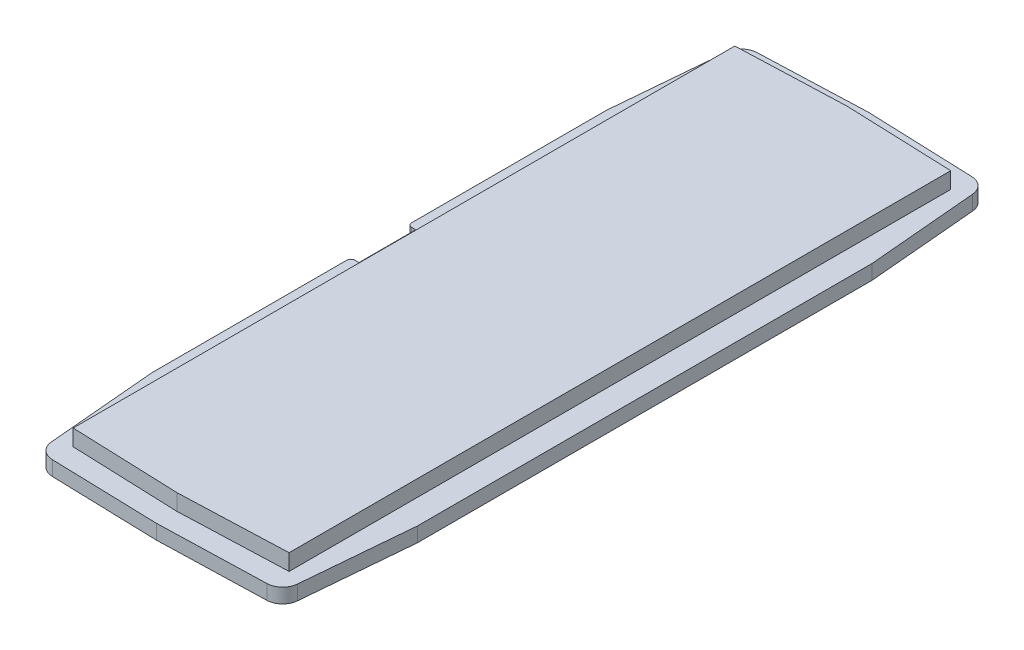
SolidWorks part; units mm, degrees
ref_plane "Спереди" through (0, 0, 0) normal (0, 0, 1) x (1, 0, 0)
ref_plane "Сверху" through (0, 0, 0) normal (0, 1, 0) x (1, 0, 0)
ref_plane "Справа" through (0, 0, 0) normal (1, 0, 0) x (0, 0, -1)
sketch "Эскиз1" plane through (0, 0, 0) normal (0, 1, 0) x (1, 0, 0)
  line L0 (-15, 43.3494) -> (-16.35, 28)
  line L1 (-16.35, 0) -> (16.35, 0) construction
  line L2 (-15.35, 3.5) -> (-15.35, -3.5)
  line L3 (-15.35, -3.5) -> (-15.85, -3.5)
  line L4 (-15.35, 3.5) -> (-15.85, 3.5)
  line L5 (-15, -43.3506) -> (0, -43.7847)
  line L6 (0, -43.7847) -> (15, -43.3506)
  line L7 (15, -43.3506) -> (16.35, -28)
  line L8 (15, 43.3494) -> (0, 43.9153)
  line L9 (0, 43.9153) -> (-15, 43.3494)
  line L10 (-16.35, 28) -> (-16.35, 4)
  line L11 (16.35, 28) -> (15, 43.3494)
  line L12 (-16.35, -28) -> (-15, -43.3506)
  line L13 (16.35, -28) -> (16.35, 28)
  line L14 (-16.35, -4) -> (-16.35, -28)
  arc A0 (-16.35, -4) -> (-15.85, -3.5) centre (-15.85, -4) cw
  arc A1 (-16.35, 4) -> (-15.85, 3.5) centre (-15.85, 4) ccw
  point P20 (-16.35, -3.5)
  dimension "D7" = 0.5
  dimension "D1" = 32.7
  dimension "D2" = 15
  dimension "D3" = 87.7
  dimension "D4" = 56
  dimension "D5" = 7
  dimension "D6" = 15
  dimension "D8" = 1
extrude "Бобышка-Вытянуть1" add sketch "Эскиз1" along normal blind 1.8
sketch "Эскиз4" plane through (0, 0, 0) normal (0, 1, 0) x (1, 0, 0)
  line L0 (-13.3, 40.75) -> (-13.3, -40.75)
  line L1 (-13.3, -40.75) -> (0, -41.25)
  line L2 (0, -41.25) -> (13.3, -40.75)
  line L3 (13.3, -40.75) -> (13.3, 40.75)
  line L4 (13.3, 40.75) -> (0, 41.25)
  line L5 (0, 41.25) -> (-13.3, 40.75)
  line L6 (-13.3, 0) -> (13.3, 0) construction
  dimension "D1" = 26.6
  dimension "D2" = 82.5
  dimension "D3" = 81.5
extrude "Бобышка-Вытянуть2" add sketch "Эскиз4" along normal blind 3.8
fillet "Скругление1" radius 2 4 edges at (15, 0.9, 43.3506) (-15, 0.9, 43.3506) (-15, 0.9, -43.3494) (15, 0.9, -43.3494)
sketch "Эскиз5" plane through (0, 3.8, 0) normal (0, 1, 0) x (-1, 0, 0)
  line L1 (-13.3, 40.75) -> (-13.3, -40.75) construction
  line L2 (3.7, 0) -> (-4.3, 0) construction
  line L3 (-0.3, -4) -> (-0.3, 4) construction
  circle A0 centre (-0.3, 0) radius 4
  point P8 (-13.3, 0)
  dimension "D1" = 8
  dimension "D2" = 13
extrude "Вырез-Вытянуть1" [suppressed] cut sketch "Эскиз5" against normal blind 4
sketch "Эскиз6" plane through (0, 3.8, 0) normal (0, 1, 0) x (1, 0, 0)
  line L0 (13.3, -40.75) -> (13.3, 40.75) construction
  circle A0 centre (0.3, 0) radius 6
  point P2 (13.3, 0)
  dimension "D1" = 12
  dimension "D2" = 13
extrude "Вырез-Вытянуть2" [suppressed] cut sketch "Эскиз6" against normal blind 1.5
sketch "Эскиз7" plane through (0, 3.8, 0) normal (0, 1, 0) x (-1, 0, 0)
  line L0 (-13.3, 40.75) -> (-13.3, -40.75) construction
  line L1 (5.2, -5) -> (-6.8, -5)
  line L2 (5.2, -5) -> (5.2, 5)
  line L3 (5.2, 5) -> (-6.8, 5)
  line L4 (-6.8, -5) -> (-6.8, 5)
  line L5 (5.2, 0) -> (-6.8, 0) construction
  point P4 (-13.3, 0)
  dimension "D1" = 10
  dimension "D2" = 12
  dimension "D3" = 6.5
extrude "Вырез-Вытянуть3" [suppressed] cut sketch "Эскиз7" against normal blind 4
